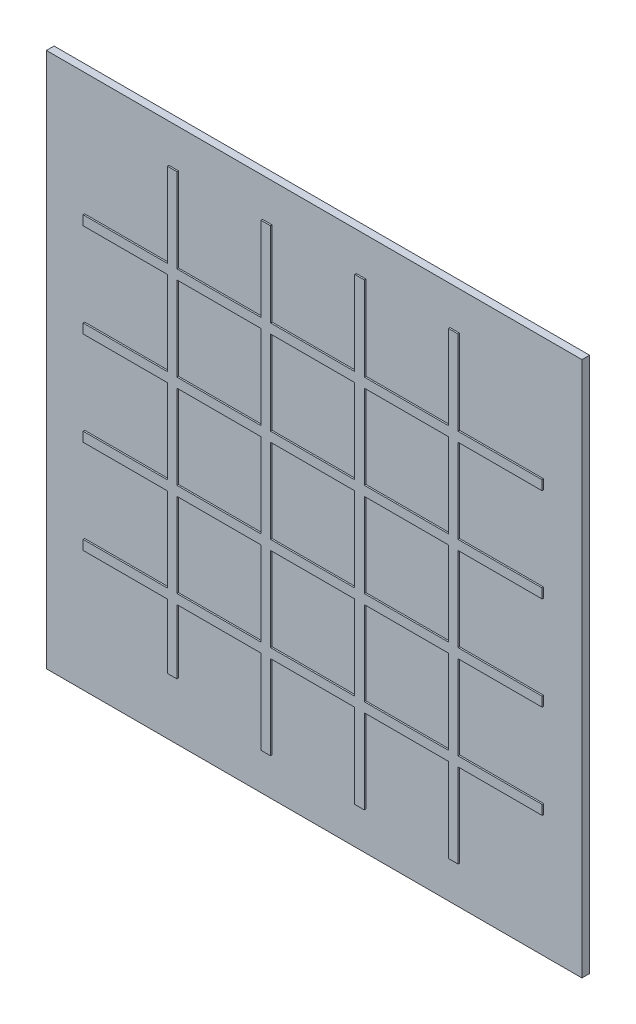
SolidWorks part; units mm, degrees
ref_plane "Front Plane" through (0, 0, 0) normal (0, 0, 1) x (1, 0, 0)
ref_plane "Top Plane" through (0, 0, 0) normal (0, 1, 0) x (1, 0, 0)
ref_plane "Right Plane" through (0, 0, 0) normal (1, 0, 0) x (0, 0, -1)
sketch "Sketch1" plane through (0, 0, 0) normal (0, 0, 1) x (1, 0, 0)
  line L1 (-66.0071, 47.0996) -> (3.9929, 47.0996)
  line L2 (-66.0071, 47.0996) -> (-66.0071, -22.9004)
  line L3 (-66.0071, -22.9004) -> (3.9929, -22.9004)
  line L4 (3.9929, 47.0996) -> (3.9929, -22.9004)
  dimension "D1" = 70
  dimension "D2" = 70
extrude "Boss-Extrude1" add sketch "Sketch1" along normal blind 1
sketch "Sketch3" plane through (0, 0, 1) normal (0, 0, 1) x (1, 0, 0)
  line L0 (-66.0071, 47.0996) -> (-66.0071, -22.9004) construction
  line L1 (-61.0071, 42.0996) -> (-1.0071, 42.0996)
  line L2 (-61.0071, 42.0996) -> (-61.0071, -17.9004)
  line L3 (-61.0071, -17.9004) -> (-1.0071, -17.9004)
  line L4 (-1.0071, 42.0996) -> (-1.0071, -17.9004)
  line L5 (3.9929, 47.0996) -> (-66.0071, 47.0996) construction
  line L6 (3.9929, -22.9004) -> (3.9929, 47.0996) construction
  line L7 (-66.0071, -22.9004) -> (3.9929, -22.9004) construction
  line L8 (-48.7571, 42.0996) -> (-37.7571, 42.0996)
  line L9 (-61.0071, 42.0996) -> (-50.0071, 42.0996)
  line L10 (-61.0071, 42.0996) -> (-61.0071, 31.0996)
  line L11 (-61.0071, 31.0996) -> (-50.0071, 31.0996)
  line L12 (-50.0071, 42.0996) -> (-50.0071, 31.0996)
  line L13 (-48.7571, 42.0996) -> (-48.7571, 31.0996)
  line L14 (-48.7571, 31.0996) -> (-37.7571, 31.0996)
  line L15 (-37.7571, 42.0996) -> (-37.7571, 31.0996)
  line L16 (-36.5071, 42.0996) -> (-25.5071, 42.0996)
  line L17 (-36.5071, 42.0996) -> (-36.5071, 31.0996)
  line L18 (-36.5071, 31.0996) -> (-25.5071, 31.0996)
  line L19 (-25.5071, 42.0996) -> (-25.5071, 31.0996)
  line L20 (-24.2571, 42.0996) -> (-13.2571, 42.0996)
  line L21 (-24.2571, 42.0996) -> (-24.2571, 31.0996)
  line L22 (-24.2571, 31.0996) -> (-13.2571, 31.0996)
  line L23 (-13.2571, 42.0996) -> (-13.2571, 31.0996)
  line L24 (-12.0071, 42.0996) -> (-1.0071, 42.0996)
  line L25 (-12.0071, 42.0996) -> (-12.0071, 31.0996)
  line L26 (-12.0071, 31.0996) -> (-1.0071, 31.0996)
  line L27 (-1.0071, 42.0996) -> (-1.0071, 31.0996)
  line L28 (-61.0071, 29.8496) -> (-50.0071, 29.8496)
  line L29 (-48.7571, 29.8496) -> (-37.7571, 29.8496)
  line L30 (-61.0071, 29.8496) -> (-50.0071, 29.8496)
  line L31 (-61.0071, 29.8496) -> (-61.0071, 18.8496)
  line L32 (-61.0071, 18.8496) -> (-50.0071, 18.8496)
  line L33 (-50.0071, 29.8496) -> (-50.0071, 18.8496)
  line L34 (-48.7571, 29.8496) -> (-48.7571, 18.8496)
  line L35 (-48.7571, 18.8496) -> (-37.7571, 18.8496)
  line L36 (-37.7571, 29.8496) -> (-37.7571, 18.8496)
  line L37 (-36.5071, 29.8496) -> (-25.5071, 29.8496)
  line L38 (-36.5071, 29.8496) -> (-36.5071, 18.8496)
  line L39 (-36.5071, 18.8496) -> (-25.5071, 18.8496)
  line L40 (-25.5071, 29.8496) -> (-25.5071, 18.8496)
  line L41 (-24.2571, 29.8496) -> (-13.2571, 29.8496)
  line L42 (-24.2571, 29.8496) -> (-24.2571, 18.8496)
  line L43 (-24.2571, 18.8496) -> (-13.2571, 18.8496)
  line L44 (-13.2571, 29.8496) -> (-13.2571, 18.8496)
  line L45 (-12.0071, 29.8496) -> (-1.0071, 29.8496)
  line L46 (-12.0071, 29.8496) -> (-12.0071, 18.8496)
  line L47 (-12.0071, 18.8496) -> (-1.0071, 18.8496)
  line L48 (-1.0071, 29.8496) -> (-1.0071, 18.8496)
  line L49 (-61.0071, 17.5996) -> (-50.0071, 17.5996)
  line L50 (-48.7571, 17.5996) -> (-37.7571, 17.5996)
  line L51 (-61.0071, 17.5996) -> (-50.0071, 17.5996)
  line L52 (-61.0071, 17.5996) -> (-61.0071, 6.5996)
  line L53 (-61.0071, 6.5996) -> (-50.0071, 6.5996)
  line L54 (-50.0071, 17.5996) -> (-50.0071, 6.5996)
  line L55 (-48.7571, 17.5996) -> (-48.7571, 6.5996)
  line L56 (-48.7571, 6.5996) -> (-37.7571, 6.5996)
  line L57 (-37.7571, 17.5996) -> (-37.7571, 6.5996)
  line L58 (-36.5071, 17.5996) -> (-25.5071, 17.5996)
  line L59 (-36.5071, 17.5996) -> (-36.5071, 6.5996)
  line L60 (-36.5071, 6.5996) -> (-25.5071, 6.5996)
  line L61 (-25.5071, 17.5996) -> (-25.5071, 6.5996)
  line L62 (-24.2571, 17.5996) -> (-13.2571, 17.5996)
  line L63 (-24.2571, 17.5996) -> (-24.2571, 6.5996)
  line L64 (-24.2571, 6.5996) -> (-13.2571, 6.5996)
  line L65 (-13.2571, 17.5996) -> (-13.2571, 6.5996)
  line L66 (-12.0071, 17.5996) -> (-1.0071, 17.5996)
  line L67 (-12.0071, 17.5996) -> (-12.0071, 6.5996)
  line L68 (-12.0071, 6.5996) -> (-1.0071, 6.5996)
  line L69 (-1.0071, 17.5996) -> (-1.0071, 6.5996)
  line L70 (-61.0071, 5.3496) -> (-50.0071, 5.3496)
  line L71 (-48.7571, 5.3496) -> (-37.7571, 5.3496)
  line L72 (-61.0071, 5.3496) -> (-50.0071, 5.3496)
  line L73 (-61.0071, 5.3496) -> (-61.0071, -5.6504)
  line L74 (-61.0071, -5.6504) -> (-50.0071, -5.6504)
  line L75 (-50.0071, 5.3496) -> (-50.0071, -5.6504)
  line L76 (-48.7571, 5.3496) -> (-48.7571, -5.6504)
  line L77 (-48.7571, -5.6504) -> (-37.7571, -5.6504)
  line L78 (-37.7571, 5.3496) -> (-37.7571, -5.6504)
  line L79 (-36.5071, 5.3496) -> (-25.5071, 5.3496)
  line L80 (-36.5071, 5.3496) -> (-36.5071, -5.6504)
  line L81 (-36.5071, -5.6504) -> (-25.5071, -5.6504)
  line L82 (-25.5071, 5.3496) -> (-25.5071, -5.6504)
  line L83 (-24.2571, 5.3496) -> (-13.2571, 5.3496)
  line L84 (-24.2571, 5.3496) -> (-24.2571, -5.6504)
  line L85 (-24.2571, -5.6504) -> (-13.2571, -5.6504)
  line L86 (-13.2571, 5.3496) -> (-13.2571, -5.6504)
  line L87 (-12.0071, 5.3496) -> (-1.0071, 5.3496)
  line L88 (-12.0071, 5.3496) -> (-12.0071, -5.6504)
  line L89 (-12.0071, -5.6504) -> (-1.0071, -5.6504)
  line L90 (-1.0071, 5.3496) -> (-1.0071, -5.6504)
  line L91 (-61.0071, -6.9004) -> (-50.0071, -6.9004)
  line L92 (-48.7571, -6.9004) -> (-37.7571, -6.9004)
  line L93 (-61.0071, -6.9004) -> (-50.0071, -6.9004)
  line L94 (-61.0071, -6.9004) -> (-61.0071, -17.9004)
  line L95 (-61.0071, -17.9004) -> (-50.0071, -17.9004)
  line L96 (-50.0071, -6.9004) -> (-50.0071, -17.9004)
  line L97 (-48.7571, -6.9004) -> (-48.7571, -17.9004)
  line L98 (-48.7571, -17.9004) -> (-37.7571, -17.9004)
  line L99 (-37.7571, -6.9004) -> (-37.7571, -17.9004)
  line L100 (-36.5071, -6.9004) -> (-25.5071, -6.9004)
  line L101 (-36.5071, -6.9004) -> (-36.5071, -17.9004)
  line L102 (-36.5071, -17.9004) -> (-25.5071, -17.9004)
  line L103 (-25.5071, -6.9004) -> (-25.5071, -17.9004)
  line L104 (-24.2571, -6.9004) -> (-13.2571, -6.9004)
  line L105 (-24.2571, -6.9004) -> (-24.2571, -17.9004)
  line L106 (-24.2571, -17.9004) -> (-13.2571, -17.9004)
  line L107 (-13.2571, -6.9004) -> (-13.2571, -17.9004)
  line L108 (-12.0071, -6.9004) -> (-1.0071, -6.9004)
  line L109 (-12.0071, -6.9004) -> (-12.0071, -17.9004)
  line L110 (-12.0071, -17.9004) -> (-1.0071, -17.9004)
  line L111 (-1.0071, -6.9004) -> (-1.0071, -17.9004)
  line L112 (-36.5071, -6.9004) -> (-25.5071, -6.9004)
  line L113 (-48.7571, 5.3496) -> (-37.7571, 5.3496)
  line L114 (-36.5071, 5.3496) -> (-25.5071, 5.3496)
  line L115 (-24.2571, -6.9004) -> (-13.2571, -6.9004)
  line L116 (-24.2571, 5.3496) -> (-13.2571, 5.3496)
  line L117 (-12.0071, 5.3496) -> (-1.0071, 5.3496)
  line L118 (-12.0071, -6.9004) -> (-1.0071, -6.9004)
  line L119 (-48.7571, 17.5996) -> (-37.7571, 17.5996)
  line L120 (-36.5071, 17.5996) -> (-25.5071, 17.5996)
  line L121 (-24.2571, 17.5996) -> (-13.2571, 17.5996)
  line L122 (-12.0071, 17.5996) -> (-1.0071, 17.5996)
  line L123 (-12.0071, 29.8496) -> (-1.0071, 29.8496)
  line L124 (-24.2571, 29.8496) -> (-13.2571, 29.8496)
  line L125 (-36.5071, 29.8496) -> (-25.5071, 29.8496)
  line L126 (-48.7571, 29.8496) -> (-37.7571, 29.8496)
  dimension "D1" = 5
  dimension "D2" = 5
  dimension "D3" = 5
  dimension "D4" = 5
  dimension "D5" = 11
  dimension "D6" = 11
  dimension "D7" = 5
  dimension "D8" = 5
extrude "Boss-Extrude2" add sketch "Sketch3" along normal blind 0.2 contours L109 L108 L4 L89 L88 L87 L68 L67 L66 L47 L46 L45 L26 L25 L1 L23 L22 L21 L19 L18 L17 L15 L14 L13 L12 L11 L2 L28 L33 L32 L49 L54 L53 L70 L75 L74 L91 L96 L3 L97 L92 L99
sketch "Sketch4" plane through (0, 0, 1.2) normal (0, 0, 1) x (1, 0, 0)
  line L1 (-53.3898, -19.4795) -> (-47.4888, -19.4795)
  line L2 (-53.3898, -19.4795) -> (-53.3898, -15.3157)
  line L3 (-53.3898, -15.3157) -> (-47.4888, -15.3157)
  line L4 (-47.4888, -19.4795) -> (-47.4888, -15.3157)
extrude "Cut-Extrude3" cut sketch "Sketch4" against normal blind 0.2
